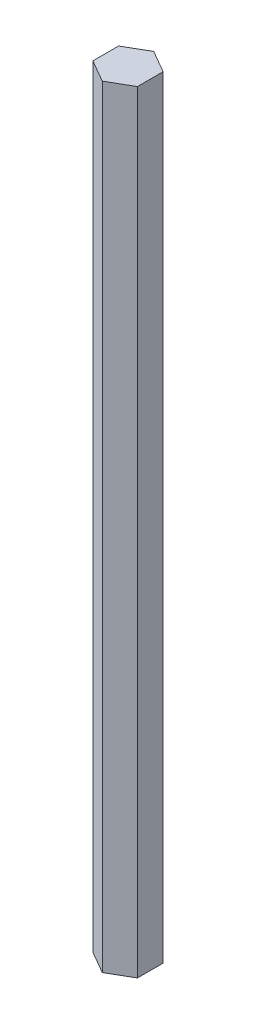
SolidWorks part; units mm, degrees
ref_plane "Front Plane" through (0, 0, 0) normal (0, 0, 1) x (1, 0, 0)
ref_plane "Top Plane" through (0, 0, 0) normal (0, 1, 0) x (1, 0, 0)
ref_plane "Right Plane" through (0, 0, 0) normal (1, 0, 0) x (0, 0, -1)
sketch "Sketch1" plane through (0, 0, 0) normal (0, 1, 0) x (1, 0, 0)
  line L1 (0, 4.7049) -> (-4.7625, 1.9553)
  line L2 (-4.7625, 1.9553) -> (-4.7625, -3.544)
  line L3 (-4.7625, -3.544) -> (0, -6.2936)
  line L4 (0, -6.2936) -> (4.7625, -3.544)
  line L5 (4.7625, -3.544) -> (4.7625, 1.9553)
  line L6 (4.7625, 1.9553) -> (0, 4.7049)
  circle A0 centre (0, -0.7943) radius 4.7625 construction
  dimension "D1" = 9.525
extrude "Boss-Extrude1" add sketch "Sketch1" along normal blind 165.1
